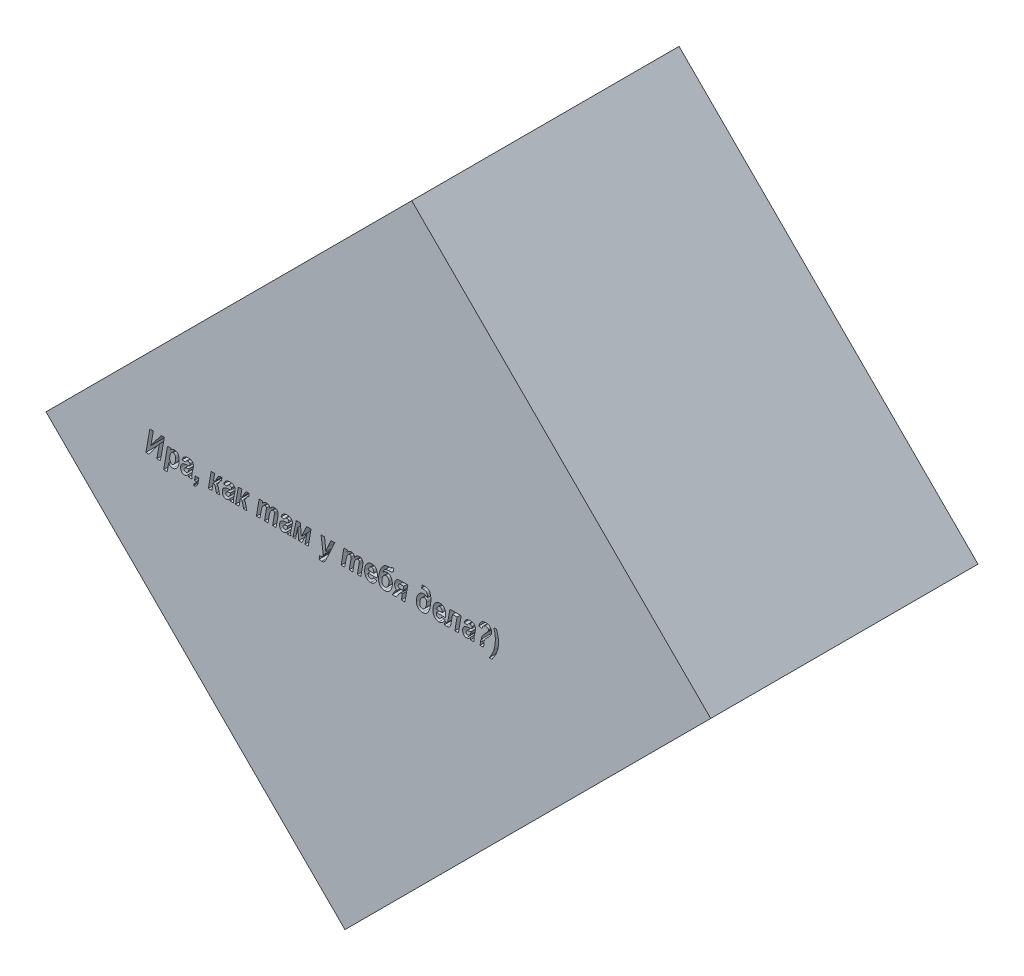
SolidWorks part; units mm, degrees
other "Детальный элемент1"
ref_plane "Спереди" through (0, 0, 0) normal (0, 0, 1) x (1, 0, 0)
ref_plane "Сверху" through (0, 0, 0) normal (0, 1, 0) x (1, 0, 0)
ref_plane "Справа" through (0, 0, 0) normal (1, 0, 0) x (0, 0, -1)
ref_plane "Плоскость1" through (0, 0, 0.6) normal (0, 0, 1) x (1, 0, 0)
sketch "Эскиз1" plane through (0, 0, 0.6) normal (0, 0, 1) x (1, 0, 0)
  line L0 (0.075, 0.746) -> (-0.746, -0.075)
  line L1 (-0.746, -0.075) -> (-0.075, -0.746)
  line L2 (-0.075, -0.746) -> (0.746, 0.075)
  line L3 (0.746, 0.075) -> (0.075, 0.746)
extrude "Бобышка-Вытянуть1" add sketch "Эскиз1" against normal blind 0.6
sketch "Эскиз2" plane through (0, 0, 0.6) normal (0, 0, 1) x (1, 0, 0)
  text T0 "Ира, как там у тебя дела?)\r\n" font "Arial Narrow" height 0.05
extrude "Вырез-Вытянуть1" cut sketch "Эскиз2" against normal blind 0.1
